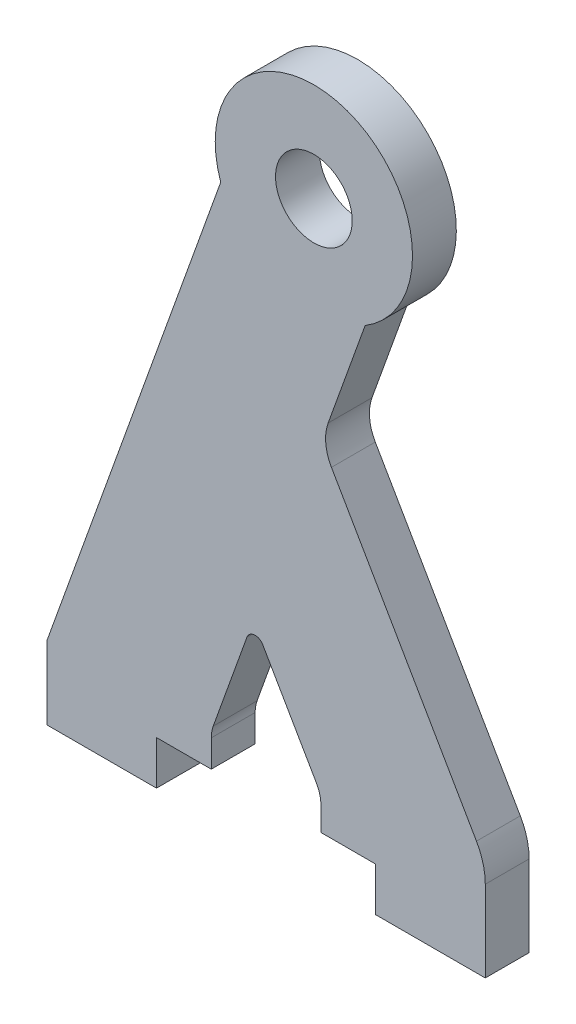
SolidWorks part; units mm, degrees
ref_plane "Front Plane" through (0, 0, 0) normal (0, 0, 1) x (1, 0, 0)
ref_plane "Top Plane" through (0, 0, 0) normal (0, 1, 0) x (1, 0, 0)
ref_plane "Right Plane" through (0, 0, 0) normal (1, 0, 0) x (0, 0, -1)
sketch "Sketch1" plane through (0, 0, 0) normal (0, 0, 1) x (1, 0, 0)
  line L0 (0, 0) -> (0, 3.3271)
  line L1 (14.5178, 23.0372) -> (7.9299, 25.4036) construction
  line L2 (0, 0) -> (5, 0)
  line L3 (5, 0) -> (5, 2)
  line L4 (5, 2) -> (7.5, 2)
  line L5 (7.5, 2) -> (7.5, 3.2388)
  line L6 (12.299, 3.8481) -> (9.849, 8.0917)
  line L7 (9.1261, 8.027) -> (7.5883, 3.7459)
  line L8 (0, 3.3271) -> (6.3118, 3.3271) construction
  line L9 (14.5178, 23.0372) -> (12.8313, 18.3421)
  line L10 (12.9815, 16.666) -> (19.5981, 5.2058)
  line L11 (12.18, 26.8823) -> (11.2238, 24.2204) construction
  line L12 (7.9299, 25.4036) -> (0, 3.3271)
  line L22 (12.5, 3.0981) -> (12.5, 2)
  line L23 (12.5, 2) -> (15, 2)
  line L24 (15, 2) -> (15, 0)
  line L25 (15, 0) -> (20, 0)
  line L26 (20, 0) -> (20, 3.7058)
  line L28 (7.5, 3.5) -> (12.5, 3.5) construction
  arc A0 (12.8313, 18.3421) -> (12.9815, 16.666) centre (14.7136, 17.666) ccw
  arc A1 (20, 3.7058) -> (19.5981, 5.2058) centre (17, 3.7058) ccw
  arc A2 (9.849, 8.0917) -> (9.1261, 8.027) centre (9.5025, 7.8917) ccw
  arc A3 (7.5, 3.2388) -> (7.5883, 3.7459) centre (9, 3.2388) cw
  arc A4 (12.299, 3.8481) -> (12.5, 3.0981) centre (11, 3.0981) cw
  circle A8 centre (12.18, 26.8823) radius 1.75
  arc A9 (14.5178, 23.0372) -> (7.9299, 25.4036) centre (12.18, 26.8823) ccw
  dimension "D5" = 7
  dimension "D6" = 7
  dimension "D8" = 9
  dimension "D9" = 3.5
  dimension "D14" = 2
  dimension "D15" = 3
  dimension "D16" = 0.4
  dimension "D17" = 1.5
  dimension "D3" = 10
  dimension "D4" = 2.82
  dimension "D7" = 7
  dimension "D10" = 5
  dimension "D11" = 1.5
  dimension "D12" = 2.5
  dimension "D13" = 5
  dimension "D18" = 2
  dimension "D19" = 60
  dimension "D21" = 24.8823
extrude "Boss-Extrude1" add sketch "Sketch1" along normal blind 2
